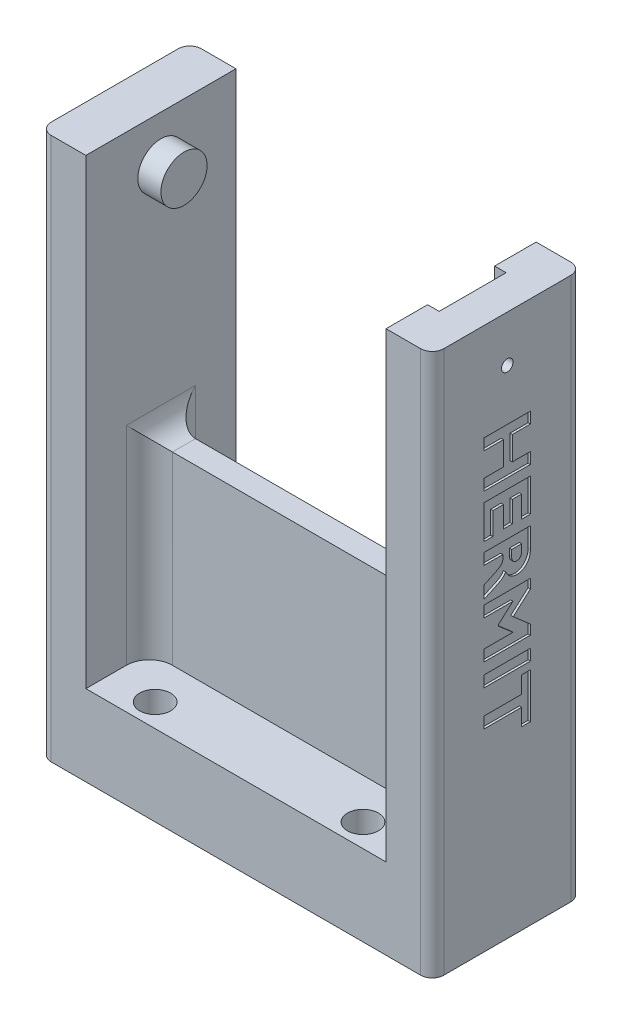
SolidWorks part; units mm, degrees
ref_plane "Front Plane" through (0, 0, 0) normal (0, 0, 1) x (1, 0, 0)
ref_plane "Top Plane" through (0, 0, 0) normal (0, 1, 0) x (1, 0, 0)
ref_plane "Right Plane" through (0, 0, 0) normal (1, 0, 0) x (0, 0, -1)
sketch "Sketch1" plane through (0, 0, 0) normal (0, 1, 0) x (1, 0, 0)
  line L1 (-42.5, -16.25) -> (42.5, -16.25)
  line L2 (-42.5, -16.25) -> (-42.5, 16.25)
  line L3 (-42.5, 16.25) -> (42.5, 16.25)
  line L4 (42.5, -16.25) -> (42.5, 16.25)
  line L5 (-42.5, -16.25) -> (42.5, 16.25) construction
  line L6 (-42.5, 16.25) -> (42.5, -16.25) construction
  point P0 (0, 0)
  dimension "D1" = 32.5
  dimension "D2" = 85
extrude "Boss-Extrude1" add sketch "Sketch1" along normal blind 10
sketch "Sketch2" plane through (0, 0, 0) normal (0, -1, 0) x (1, 0, 0)
  line L0 (0, 0) -> (0, -16.25) construction
  line L1 (42.5, -16.25) -> (-42.5, -16.25) construction
  circle A0 centre (-10, 0) radius 2.25
  circle A6 centre (-10, 0) radius 4.125
  circle A7 centre (10, 0) radius 4.125
  circle A8 centre (10, 0) radius 2.25
  dimension "D1" = 4.5
  dimension "D2" = 8.25
  dimension "D3" = 10
extrude "Boss-Extrude2" add sketch "Sketch2" along normal blind 7.5
sketch "Sketch3" plane through (0, 10, 0) normal (0, 1, 0) x (1, 0, 0)
  line L0 (-42.5, -16.25) -> (42.5, -16.25) construction
  line L1 (-42.5, 16.25) -> (-32.5, 16.25)
  line L2 (-42.5, 16.25) -> (-42.5, -16.25)
  line L3 (-42.5, -16.25) -> (-32.5, -16.25)
  line L4 (-32.5, 16.25) -> (-32.5, -16.25)
  line L6 (42.5, 16.25) -> (32.5, 16.25)
  line L7 (42.5, 16.25) -> (42.5, -16.25)
  line L8 (42.5, -16.25) -> (32.5, -16.25)
  line L9 (32.5, 16.25) -> (32.5, -16.25)
  dimension "D1" = 10
extrude "Boss-Extrude3" add sketch "Sketch3" along normal blind 100
sketch "Sketch5" plane through (-32.5, 0, 0) normal (1, 0, 0) x (0, 0, -1)
  line L0 (-16.25, 110) -> (16.25, 110) construction
  line L1 (-16.25, 10) -> (16.25, 10) construction
  circle A0 centre (0, 100) radius 5
  point P6 (0, 10)
  dimension "D1" = 10
  dimension "D2" = 10
extrude "Boss-Extrude4" add sketch "Sketch5" along normal blind 5
sketch "Sketch7" plane through (32.5, 0, 0) normal (1, 0, 0) x (0, 0, -1)
  line L0 (0, 100) -> (0, 90.5)
  line L1 (7.25, 100) -> (7.25, 110)
  line L2 (7.25, 110) -> (-7.25, 110)
  line L3 (-7.25, 110) -> (-7.25, 100)
  line L4 (-16.25, 110) -> (16.25, 110) construction
  line L5 (5.25, 69) -> (7.25, 100)
  line L6 (-7.25, 100) -> (-5.25, 69)
  circle A0 centre (0, 90.5) radius 1 construction
  circle A1 centre (0, 100) radius 5
  circle A2 centre (0, 100) radius 5 construction
  circle A3 centre (0, 85.5) radius 1 construction
  circle A4 centre (0, 100) radius 7.25
  circle A5 centre (0, 69) radius 5.25
  dimension "D2" = 2
  dimension "D5" = 14.5
  dimension "D6" = 10.5
  dimension "D3" = 9.5
  dimension "D4" = 5
  dimension "D7" = 31
  dimension "D1" = 0
sketch "Sketch8" plane through (0, 10, 0) normal (0, 1, 0) x (1, 0, 0)
  circle A0 centre (-22.5, 11.25) radius 2.125 construction
  circle A1 centre (-22.5, -11.25) radius 2.125 construction
  circle A2 centre (22.5, 11.25) radius 2.125 construction
  circle A3 centre (22.5, -11.25) radius 2.125 construction
  circle A4 centre (-22.5, 11.25) radius 2.125
  circle A5 centre (-22.5, -11.25) radius 2.125
  circle A6 centre (22.5, 11.25) radius 2.125
  circle A7 centre (22.5, -11.25) radius 2.125
sketch "Sketch9" plane through (0, 10, 0) normal (0, 1, 0) x (1, 0, 0)
  point P0 (-22.5, 11.25)
  point P3 (22.5, 11.25)
  point P6 (22.5, -11.25)
  point P9 (-22.5, -11.25)
hole_wizard "CBORE for M3 SBHCS1" positions "Sketch9" profile "Sketch10" counterbore size "M3" standard "ANSI Metric" end condition through all
sketch "Sketch10" plane through (-22.5, 10, -11.25) normal (1, 0, 0) x (0, 0, 1)
  line L0 (0, 0) -> (0, 17.5)
  line L1 (0, 17.5) -> (1.8, 17.5)
  line L3 (1.8, 17.5) -> (1.8, 9.15)
  line L4 (1.8, 9.15) -> (3.35, 9.15)
  line L5 (3.35, 9.15) -> (3.35, 0)
  line L7 (3.35, 0) -> (0, 0)
  line L11 (0, -6.35) -> (0, 107.95) construction
  dimension "Thru Hole Dia." = 3.6
  dimension "Thru Hole Depth" = 17.5
  dimension "C'Bore Dia." = 6.7
  dimension "C'Bore Depth" = 9.15
extrude "Cut-Extrude1" cut sketch "Sketch7" along normal blind 2.5
sketch "Sketch11" plane through (42.5, 0, 0) normal (1, 0, 0) x (0, 0, -1)
  circle A1 centre (0, 100) radius 5
  circle A2 centre (0, 100) radius 5
  circle A4 centre (0, 120.3) radius 5.618
  point P2 (0, 100)
  point P31 (0, 120.3)
  dimension "D2" = 20.3
  dimension "D1" = 0
hole_wizard "Ø2.5mm Dowel Hole5" positions "Sketch11" profile "Sketch12" hole size "Ø2.5" standard "ANSI Metric"
sketch "Sketch12" plane through (42.5, 100, 0) normal (0, 1, 0) x (0, 0, -1)
  line L0 (0, 0) -> (0, 8.2511)
  line L1 (0, 8.2511) -> (1.25, 7.5)
  line L2 (1.25, 7.5) -> (1.25, 0)
  line L5 (1.25, 0) -> (0, 0)
  line L10 (0, 8.2511) -> (-1.25, 7.5) construction
  line L11 (0, -6.35) -> (0, 107.95) construction
  dimension "Hole Dia." = 2.5
  dimension "Hole Depth" = 7.5
  dimension "Drill Angle" = 118
sketch "Sketch13" plane through (0, 10, 0) normal (0, 1, 0) x (1, 0, 0)
  line L0 (32.5, 16.25) -> (32.5, -16.25) construction
  line L1 (-32.5, -2.5) -> (32.5, -2.5)
  line L2 (-32.5, -2.5) -> (-32.5, 2.5)
  line L3 (-32.5, 2.5) -> (32.5, 2.5)
  line L4 (32.5, -2.5) -> (32.5, 2.5)
  line L5 (-32.5, -2.5) -> (32.5, 2.5) construction
  line L6 (-32.5, 2.5) -> (32.5, -2.5) construction
  point P0 (0, 0)
  dimension "D1" = 5
extrude "Boss-Extrude5" add sketch "Sketch13" along normal blind 40
fillet "Fillet1" radius 2.5 4 edges at (-42.5, 51.25, -16.25) (42.5, 51.25, -16.25) (42.5, 51.25, 16.25) (-42.5, 51.25, 16.25)
fillet "Fillet2" radius 5 6 edges at (-32.5, 50, 0) (32.5, 50, 0) (32.5, 30, -2.5) (32.5, 30, 2.5) (-32.5, 30, -2.5) (-32.5, 30, 2.5)
sketch "Sketch14" plane through (-42.5, 0, 0) normal (-1, 0, 0) x (0, 0, 1)
  line L0 (0, 0) -> (0, 94.1215) construction
  line L1 (-4.125, 0) -> (4.125, 0) construction
  line L2 (5, 90) -> (5, 0)
  line L3 (-5, 89.5946) -> (-3.1081, 89.5946)
  line L4 (-3.1081, 89.5946) -> (-3.1081, 85.9459)
  line L5 (-3.1081, 85.9459) -> (5, 85.9459)
  line L6 (5, 85.9459) -> (5, 83.5135)
  line L7 (5, 83.5135) -> (-3.1081, 83.5135)
  line L8 (-3.1081, 83.5135) -> (-3.1081, 79.8649)
  line L9 (-3.1081, 79.8649) -> (-5, 79.8649)
  line L10 (-5, 79.8649) -> (-5, 89.5946)
  line L11 (-5, 78.2432) -> (5, 78.2432)
  line L12 (5, 78.2432) -> (5, 75.8108)
  line L13 (5, 75.8108) -> (-5, 75.8108)
  line L14 (-5, 75.8108) -> (-5, 78.2432)
  line L15 (-1.2796, 68.0405) -> (-5, 71.288)
  line L16 (-5, 71.288) -> (-5, 73.3784)
  line L17 (-5, 73.3784) -> (5, 73.3784)
  line L18 (5, 73.3784) -> (5, 70.9459)
  line L19 (5, 70.9459) -> (-1.2289, 70.9459)
  line L20 (-1.2289, 70.9459) -> (1.8919, 68.2348)
  line L21 (1.8919, 68.2348) -> (1.8919, 67.8948)
  line L22 (1.8919, 67.8948) -> (-1.2289, 65.1351)
  line L23 (-1.2289, 65.1351) -> (5, 65.1351)
  line L24 (5, 65.1351) -> (5, 62.7027)
  line L25 (5, 62.7027) -> (-5, 62.7027)
  line L26 (-5, 62.7027) -> (-5, 64.7361)
  line L27 (-5, 64.7361) -> (-1.2796, 68.0405)
  line L28 (-5, 52.8378) -> (-5, 57.2846)
  line L29 (5, 61.6216) -> (5, 58.9379)
  line L30 (0.9459, 56.0198) -> (0.9459, 55.2703)
  line L31 (0.9459, 55.2703) -> (5, 55.2703)
  line L32 (5, 55.2703) -> (5, 52.8378)
  line L33 (5, 52.8378) -> (-5, 52.8378)
  line L34 (-3.1081, 55.2703) -> (-0.9459, 55.2703)
  line L35 (-0.9459, 55.2703) -> (-0.9459, 56.5963)
  line L36 (-3.1081, 56.5393) -> (-3.1081, 55.2703)
  line L37 (3.1081, 50.8108) -> (5, 50.8108)
  line L38 (5, 50.8108) -> (5, 43.5135)
  line L39 (5, 43.5135) -> (-5, 43.5135)
  line L40 (-5, 43.5135) -> (-5, 50.6757)
  line L41 (-5, 50.6757) -> (-3.1081, 50.6757)
  line L42 (-3.1081, 50.6757) -> (-3.1081, 45.9459)
  line L43 (-3.1081, 45.9459) -> (-1.0811, 45.9459)
  line L44 (-1.0811, 45.9459) -> (-1.0811, 50.5405)
  line L45 (-1.0811, 50.5405) -> (0.8108, 50.5405)
  line L46 (0.8108, 50.5405) -> (0.8108, 45.9459)
  line L47 (0.8108, 45.9459) -> (3.1081, 45.9459)
  line L48 (3.1081, 45.9459) -> (3.1081, 50.8108)
  line L49 (-5, 41.3514) -> (5, 41.3514)
  line L50 (5, 41.3514) -> (5, 38.9189)
  line L51 (5, 38.9189) -> (0.8108, 38.9189)
  line L52 (0.8108, 38.9189) -> (0.8108, 33.7838)
  line L53 (0.8108, 33.7838) -> (5, 33.7838)
  line L54 (5, 33.7838) -> (5, 31.3514)
  line L55 (5, 31.3514) -> (-5, 31.3514)
  line L56 (-5, 31.3514) -> (-5, 33.7838)
  line L57 (-5, 33.7838) -> (-1.0811, 33.7838)
  line L58 (-1.0811, 33.7838) -> (-1.0811, 38.9189)
  line L59 (-1.0811, 38.9189) -> (-5, 38.9189)
  line L60 (-5, 38.9189) -> (-5, 41.3514)
  spline S0 degree 3 poles (-5, 57.2846) (-5.0018, 57.5151) (-4.9749, 57.8546) (-4.8881, 58.2915) (-4.7942, 58.5952) (-4.6758, 58.8817) (-4.5317, 59.1518) (-4.3599, 59.4047) (-4.1613, 59.6364) (-3.9483, 59.8496) (-3.7195, 60.0342) (-3.4786, 60.1888) (-3.2289, 60.3198) (-2.9657, 60.419) (-2.5963, 60.5127) (-2.309, 60.5401) (-2.1157, 60.5405) knots 0 0 0 0 0.142178 0.209578 0.274583 0.338083 0.400674 0.463217 0.526414 0.588781 0.649035 0.707485 0.765199 0.822814 0.880666 1 1 1 1
  spline S1 degree 3 poles (-2.1157, 60.5405) (-1.8548, 60.5394) (-1.4666, 60.4931) (-0.9902, 60.3064) (-0.6657, 60.1165) (-0.3688, 59.8721) (0.0005, 59.4584) (0.213, 59.0846) (0.3378, 58.8197) knots 0 0 0 0 0.246231 0.362922 0.479674 0.598833 0.72368 1 1 1 1
  spline S2 degree 3 poles (0.3378, 58.8197) (0.4011, 58.9635) (0.5306, 59.174) (0.7624, 59.4228) (0.9744, 59.6149) (1.2263, 59.796) (1.5094, 59.9795) (1.8313, 60.1528) (2.304, 60.377) (2.9105, 60.6485) (3.8519, 61.0811) (4.5451, 61.4074) (5, 61.6216) knots 0 0 0 0 0.085159 0.132713 0.184067 0.240028 0.300806 0.366913 0.438106 0.584498 0.72729 1 1 1 1
  spline S3 degree 3 poles (5, 58.9379) (4.8994, 58.8886) (4.7357, 58.807) (4.4967, 58.6952) (4.2767, 58.5911) (4.0284, 58.4753) (3.7518, 58.3487) (3.4473, 58.2118) (3.1253, 58.0662) (2.8034, 57.9196) (2.5044, 57.7719) (2.235, 57.6306) (1.9962, 57.4943) (1.7891, 57.3616) (1.6129, 57.2347) (1.4652, 57.1151) (1.3135, 56.9634) (1.1671, 56.7707) (0.9981, 56.4533) (0.9464, 56.1915) (0.9459, 56.0198) knots 0 0 0 0 0.064254 0.104873 0.15127 0.20381 0.261959 0.32572 0.395258 0.464597 0.528489 0.586438 0.639048 0.686065 0.727397 0.763516 0.794907 0.850198 0.901643 1 1 1 1
  spline S4 degree 3 poles (-0.9459, 56.5963) (-0.9459, 56.7869) (-0.9713, 57.0645) (-1.0955, 57.3982) (-1.2198, 57.6029) (-1.3773, 57.7699) (-1.6403, 57.934) (-1.8759, 57.974) (-2.0334, 57.973) knots 0 0 0 0 0.289522 0.416005 0.536094 0.649909 0.760505 1 1 1 1
  spline S5 degree 3 poles (-2.0334, 57.973) (-2.1919, 57.9698) (-2.4311, 57.94) (-2.6951, 57.7789) (-2.85, 57.6163) (-2.9674, 57.4076) (-3.0858, 57.0499) (-3.1072, 56.7492) (-3.1081, 56.5393) knots 0 0 0 0 0.235918 0.341315 0.448878 0.562448 0.690374 1 1 1 1
  dimension "D1" = 5
  dimension "D2" = 90
extrude "Cut-Extrude4" cut sketch "Sketch14" against normal blind 0.5 contours L0 L7 L2 L5 | L7 L0 L5 L4 L3 L10 L9 L8 | L0 L13 L2 L11 | L13 L0 L11 L14 | L0 L19 L2 L17 | L25 L0 L23 L22 L20 L19 L17 L16 L15 L27 L26 | L0 L22 L21 L20 | L0 L25 L2 L23 | L0 L33 L2 L31 L30 S3 S2 S1 | L33 L0 S1 S0 L28 S5 S4 L35 L34 L36 | L0 L39 L2 L37 L48 L47 L46 L45 | L39 L0 L45 L44 L43 L42 L41 L40 | L0 L55 L2 L53 L52 L51 L49 | L55 L0 L49 L60 L59 L58 L57 L56
sketch "Sketch16" plane through (42.5, 0, 0) normal (1, 0, 0) x (0, 0, -1)
  line L0 (0, 0) -> (0, 71.616) construction
  line L1 (-4.125, 0) -> (4.125, 0) construction
  line L2 (-5, 0) -> (-5, 90) construction
  line L3 (5, 78.9189) -> (-5, 78.9189)
  line L4 (-5, 78.9189) -> (-5, 81.3514)
  line L5 (-5, 81.3514) -> (-0.8108, 81.3514)
  line L6 (-0.8108, 81.3514) -> (-0.8108, 86.4865)
  line L7 (-0.8108, 86.4865) -> (-5, 86.4865)
  line L8 (-5, 86.4865) -> (-5, 88.9189)
  line L9 (-5, 88.9189) -> (5, 88.9189)
  line L10 (5, 88.9189) -> (5, 86.4865)
  line L11 (5, 86.4865) -> (1.0811, 86.4865)
  line L12 (1.0811, 86.4865) -> (1.0811, 81.3514)
  line L13 (1.0811, 81.3514) -> (5, 81.3514)
  line L14 (5, 81.3514) -> (5, 78.9189)
  line L15 (-3.1081, 69.4595) -> (-5, 69.4595)
  line L16 (-5, 69.4595) -> (-5, 76.7568)
  line L17 (-5, 76.7568) -> (5, 76.7568)
  line L18 (5, 76.7568) -> (5, 69.5946)
  line L19 (5, 69.5946) -> (3.1081, 69.5946)
  line L20 (3.1081, 69.5946) -> (3.1081, 74.3243)
  line L21 (3.1081, 74.3243) -> (1.0811, 74.3243)
  line L22 (1.0811, 74.3243) -> (1.0811, 69.7297)
  line L23 (1.0811, 69.7297) -> (-0.8108, 69.7297)
  line L24 (-0.8108, 69.7297) -> (-0.8108, 74.3243)
  line L25 (-0.8108, 74.3243) -> (-3.1081, 74.3243)
  line L26 (-3.1081, 74.3243) -> (-3.1081, 69.4595)
  line L27 (5, 67.4324) -> (5, 62.9856)
  line L28 (-5, 58.6486) -> (-5, 61.3323)
  line L29 (-0.9459, 64.2504) -> (-0.9459, 65)
  line L30 (-0.9459, 65) -> (-5, 65)
  line L31 (-5, 65) -> (-5, 67.4324)
  line L32 (-5, 67.4324) -> (5, 67.4324)
  line L33 (3.1081, 65) -> (0.9459, 65)
  line L34 (0.9459, 65) -> (0.9459, 63.674)
  line L35 (3.1081, 63.731) -> (3.1081, 65)
  line L36 (1.2796, 52.2297) -> (5, 48.9823)
  line L37 (5, 48.9823) -> (5, 46.8919)
  line L38 (5, 46.8919) -> (-5, 46.8919)
  line L39 (-5, 46.8919) -> (-5, 49.3243)
  line L40 (-5, 49.3243) -> (1.2289, 49.3243)
  line L41 (1.2289, 49.3243) -> (-1.8919, 52.0355)
  line L42 (-1.8919, 52.0355) -> (-1.8919, 52.3754)
  line L43 (-1.8919, 52.3754) -> (1.2289, 55.1351)
  line L44 (1.2289, 55.1351) -> (-5, 55.1351)
  line L45 (-5, 55.1351) -> (-5, 57.5676)
  line L46 (-5, 57.5676) -> (5, 57.5676)
  line L47 (5, 57.5676) -> (5, 55.5342)
  line L48 (5, 55.5342) -> (1.2796, 52.2297)
  line L49 (5, 42.027) -> (-5, 42.027)
  line L50 (-5, 42.027) -> (-5, 44.4595)
  line L51 (-5, 44.4595) -> (5, 44.4595)
  line L52 (5, 44.4595) -> (5, 42.027)
  line L53 (5, 30.6757) -> (3.1081, 30.6757)
  line L54 (3.1081, 30.6757) -> (3.1081, 34.3243)
  line L55 (3.1081, 34.3243) -> (-5, 34.3243)
  line L56 (-5, 34.3243) -> (-5, 36.7568)
  line L57 (-5, 36.7568) -> (3.1081, 36.7568)
  line L58 (3.1081, 36.7568) -> (3.1081, 40.4054)
  line L59 (3.1081, 40.4054) -> (5, 40.4054)
  line L60 (5, 40.4054) -> (5, 30.6757)
  spline S0 degree 3 poles (5, 62.9856) (5.0018, 62.7552) (4.9749, 62.4157) (4.8881, 61.9788) (4.7942, 61.6751) (4.6759, 61.3885) (4.5311, 61.1182) (4.3605, 60.8638) (4.1619, 60.6319) (3.9477, 60.4205) (3.7188, 60.2365) (3.4799, 60.0786) (3.2282, 59.9511) (2.9658, 59.8511) (2.5963, 59.7577) (2.3091, 59.7301) (2.1157, 59.7297) knots 0 0 0 0 0.142165 0.209558 0.274557 0.338052 0.400636 0.463534 0.526724 0.58878 0.649029 0.707711 0.76522 0.82283 0.880677 1 1 1 1
  spline S1 degree 3 poles (2.1157, 59.7297) (1.8548, 59.7309) (1.4666, 59.7772) (0.9902, 59.9639) (0.6657, 60.1537) (0.3688, 60.3982) (-0.0005, 60.8119) (-0.213, 61.1857) (-0.3378, 61.4506) knots 0 0 0 0 0.246231 0.362922 0.479674 0.598833 0.72368 1 1 1 1
  spline S2 degree 3 poles (-0.3378, 61.4506) (-0.4011, 61.3068) (-0.5306, 61.0962) (-0.7624, 60.8474) (-0.9744, 60.6555) (-1.2266, 60.4735) (-1.5109, 60.2921) (-1.832, 60.1161) (-2.306, 59.8946) (-2.9113, 59.6213) (-3.8539, 59.1926) (-4.5438, 58.8609) (-5, 58.6486) knots 0 0 0 0 0.08516 0.132715 0.18407 0.240032 0.301132 0.366905 0.438442 0.584837 0.727124 1 1 1 1
  spline S3 degree 3 poles (-5, 61.3323) (-4.8994, 61.3817) (-4.7357, 61.4634) (-4.4967, 61.5749) (-4.2773, 61.6797) (-4.0283, 61.7917) (-3.7536, 61.9203) (-3.4494, 62.0564) (-3.1268, 62.2015) (-2.806, 62.351) (-2.5061, 62.4989) (-2.2354, 62.6392) (-1.9963, 62.776) (-1.7891, 62.9086) (-1.6129, 63.0356) (-1.4652, 63.1552) (-1.3135, 63.3069) (-1.1663, 63.4999) (-0.9995, 63.8183) (-0.9453, 64.079) (-0.9459, 64.2504) knots 0 0 0 0 0.064257 0.104877 0.151275 0.203648 0.261433 0.325196 0.394737 0.464249 0.528143 0.586451 0.639063 0.686082 0.727416 0.763536 0.794928 0.85022 0.902026 1 1 1 1
  spline S4 degree 3 poles (0.9459, 63.674) (0.9462, 63.4836) (0.9709, 63.2055) (1.0959, 62.8727) (1.2174, 62.6668) (1.3756, 62.4997) (1.6402, 62.3373) (1.8756, 62.2957) (2.0334, 62.2973) knots 0 0 0 0 0.289421 0.415859 0.535351 0.649127 0.760589 1 1 1 1
  spline S5 degree 3 poles (2.0334, 62.2973) (2.1919, 62.3005) (2.4311, 62.3303) (2.6951, 62.4914) (2.85, 62.654) (2.9674, 62.8627) (3.0858, 63.2204) (3.1072, 63.5211) (3.1081, 63.731) knots 0 0 0 0 0.235918 0.341315 0.448878 0.562448 0.690374 1 1 1 1
  dimension "D1" = 5
  dimension "D2" = 90
extrude "Cut-Extrude5" cut sketch "Sketch16" against normal blind 0.5
